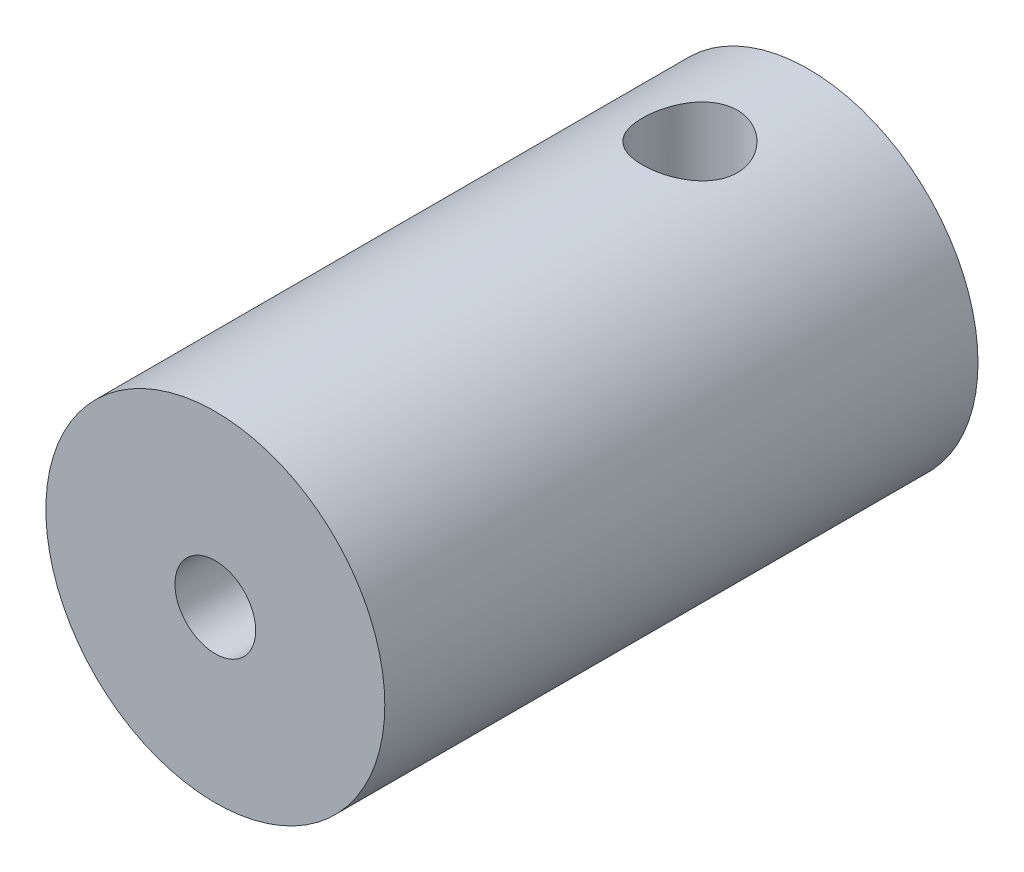
SolidWorks part; units mm, degrees
ref_plane "Front Plane" through (0, 0, 0) normal (0, 0, 1) x (1, 0, 0)
ref_plane "Top Plane" through (0, 0, 0) normal (0, 1, 0) x (1, 0, 0)
ref_plane "Right Plane" through (0, 0, 0) normal (1, 0, 0) x (0, 0, -1)
sketch "Sketch1" plane through (0, 0, 0) normal (0, 0, 1) x (1, 0, 0)
  circle A0 centre (0, 0) radius 10
  dimension "D1" = 20
extrude "Boss-Extrude1" add sketch "Sketch1" along normal blind 35
ref_plane "Plane1" through (0, 0, 12) normal (0, 0, 1) x (1, 0, 0)
sketch "Sketch2" plane through (0, 0, 12) normal (0, 0, 1) x (1, 0, 0)
  circle A0 centre (0, 0) radius 2.9
  dimension "D1" = 5.8
extrude "Cut-Extrude1" cut sketch "Sketch2" against normal up to surface (12 mm away) draft 1 contours A0
sketch "Sketch4" plane through (0, 0, 35) normal (0, 0, 1) x (1, 0, 0)
  circle A0 centre (0, 0) radius 2.3813
  dimension "D1" = 4.7625
extrude "Cut-Extrude2" cut sketch "Sketch4" against normal blind 35
sketch "Sketch5" plane through (0, 0, 0) normal (0, 1, 0) x (1, 0, 0)
  line L0 (0, 0) -> (0, -12) construction
  line L1 (10, 0) -> (-10, 0) construction
  line L2 (-11, -12) -> (11, -12) construction
  circle A0 centre (0, -7) radius 2.8
  point P8 (0, -5.4989)
  point P9 (0, -4.7484)
  dimension "D1" = 5.6
  dimension "D2" = 5
extrude "Cut-Extrude3" cut sketch "Sketch5" along normal through all
